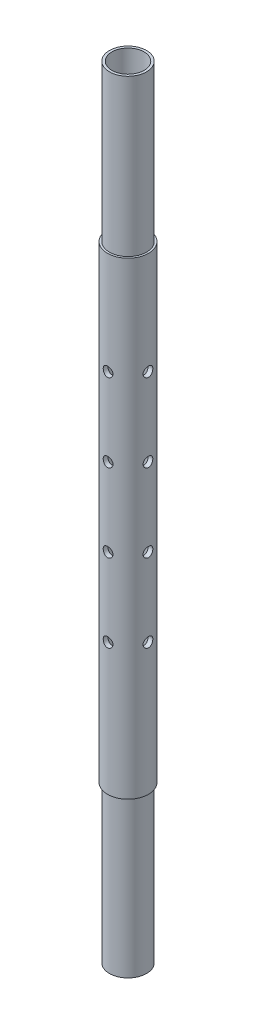
SolidWorks part; units mm, degrees
ref_plane "Front Plane" through (0, 0, 0) normal (0, 0, 1) x (1, 0, 0)
ref_plane "Top Plane" through (0, 0, 0) normal (0, 1, 0) x (1, 0, 0)
ref_plane "Right Plane" through (0, 0, 0) normal (1, 0, 0) x (0, 0, -1)
sketch "Sketch1" plane through (0, 0, 0) normal (0, 1, 0) x (1, 0, 0)
  circle A0 centre (0, 0) radius 13.335
  circle A1 centre (0, 0) radius 10.4648
  dimension "D1" = 26.67
  dimension "D2" = 2.8702
extrude "Boss-Extrude1" add sketch "Sketch1" along normal mid plane 508
sketch "Sketch2" plane through (0, 0, 0) normal (0, 0, 1) x (1, 0, 0)
  line L0 (-178.095, 0) -> (178.095, 0) construction
  line L1 (0, -321.7876) -> (0, 321.7876) construction
  line L2 (-62.2592, -152.4) -> (62.2592, -152.4) construction
  line L3 (-62.2592, -66.675) -> (62.2592, -66.675) construction
  line L4 (-65.9857, -15.875) -> (65.9857, -15.875) construction
  line L5 (-78.4073, 34.925) -> (78.4073, 34.925) construction
  line L6 (-13.335, -254) -> (13.335, -254) construction
  line L7 (-75.6739, 85.725) -> (75.6739, 85.725) construction
  line L8 (-88.1047, 149.225) -> (88.1047, 149.225) construction
  line L9 (-129.0131, 250.825) -> (129.0131, 250.825) construction
  circle A0 centre (0, -66.675) radius 3.175
  circle A1 centre (0, -15.875) radius 3.175
  circle A2 centre (0, 34.925) radius 3.175
  circle A3 centre (0, 85.725) radius 3.175
  point P4 (0, 0)
  point P8 (0, 0)
  point P11 (0, -152.4)
  point P14 (0, -66.675)
  point P17 (0, -15.875)
  point P20 (0, 34.925)
  point P25 (0, 85.725)
  point P28 (0, 149.225)
  point P31 (0, 250.825)
  dimension "D8" = 6.35
  dimension "D1" = 101.6
  dimension "D2" = 85.725
  dimension "D3" = 50.8
  dimension "D4" = 50.8
  dimension "D5" = 50.8
  dimension "D6" = 63.5
  dimension "D7" = 101.6
  dimension "D9" = 4
extrude "Cut-Extrude1" cut sketch "Sketch2" against normal mid plane 127
sketch "Sketch3" plane through (0, 0, 0) normal (1, 0, 0) x (0, 0, -1)
  line L0 (-192.9623, 0) -> (192.9623, 0) construction
  line L1 (0, -277.3935) -> (0, 277.3935) construction
  line L2 (-89.6837, -152.4) -> (89.6837, -152.4) construction
  line L3 (-98.4488, -66.675) -> (98.4488, -66.675) construction
  line L4 (-71.49, 149.225) -> (71.49, 149.225) construction
  line L5 (-98.4488, -15.875) -> (98.4488, -15.875) construction
  line L6 (-98.4488, 34.925) -> (98.4488, 34.925) construction
  line L7 (-98.4488, 85.725) -> (98.4488, 85.725) construction
  line L8 (-13.335, -254) -> (13.335, -254) construction
  line L9 (-71.49, 250.825) -> (71.49, 250.825) construction
  circle A0 centre (0, -66.675) radius 3.175
  circle A1 centre (0, -15.875) radius 3.175
  circle A2 centre (0, 34.925) radius 3.175
  circle A3 centre (0, 85.725) radius 3.175
  point P4 (0, 0)
  point P8 (0, 0)
  point P11 (0, -152.4)
  point P14 (0, -66.675)
  point P17 (0, -76.5821)
  point P20 (0, -15.875)
  point P23 (0, 34.925)
  point P26 (0, 85.725)
  point P28 (0, 149.225)
  point P31 (0, 250.825)
  dimension "D8" = 6.35
  dimension "D1" = 101.6
  dimension "D2" = 85.725
  dimension "D3" = 50.8
  dimension "D4" = 50.8
  dimension "D5" = 50.8
  dimension "D6" = 63.5
  dimension "D7" = 101.6
  dimension "D9" = 4
extrude "Cut-Extrude2" cut sketch "Sketch3" against normal mid plane 127
sketch "Sketch4" plane through (0, 254, 0) normal (0, 1, 0) x (1, 0, 0)
  line L0 (-46.3542, 0) -> (46.3542, 0) construction
  line L1 (0, -42.7267) -> (0, 42.7267) construction
  circle A0 centre (0, 0) radius 12.065
  circle A1 centre (0, 0) radius 13.335
  point P6 (0, 0)
  point P10 (0, 0)
  dimension "D1" = 24.13
extrude "Cut-Extrude3" cut sketch "Sketch4" against normal blind 101.6
sketch "Sketch5" plane through (0, -254, 0) normal (0, -1, 0) x (1, 0, 0)
  line L0 (-23.9177, 0) -> (23.9177, 0) construction
  line L1 (0, -20.7348) -> (0, 20.7348) construction
  circle A0 centre (0, 0) radius 12.065
  circle A1 centre (0, 0) radius 13.335
  point P5 (0, 0)
  point P6 (0, 0)
  point P9 (0, 0)
  dimension "D1" = 24.13
extrude "Cut-Extrude4" cut sketch "Sketch5" against normal blind 101.6
